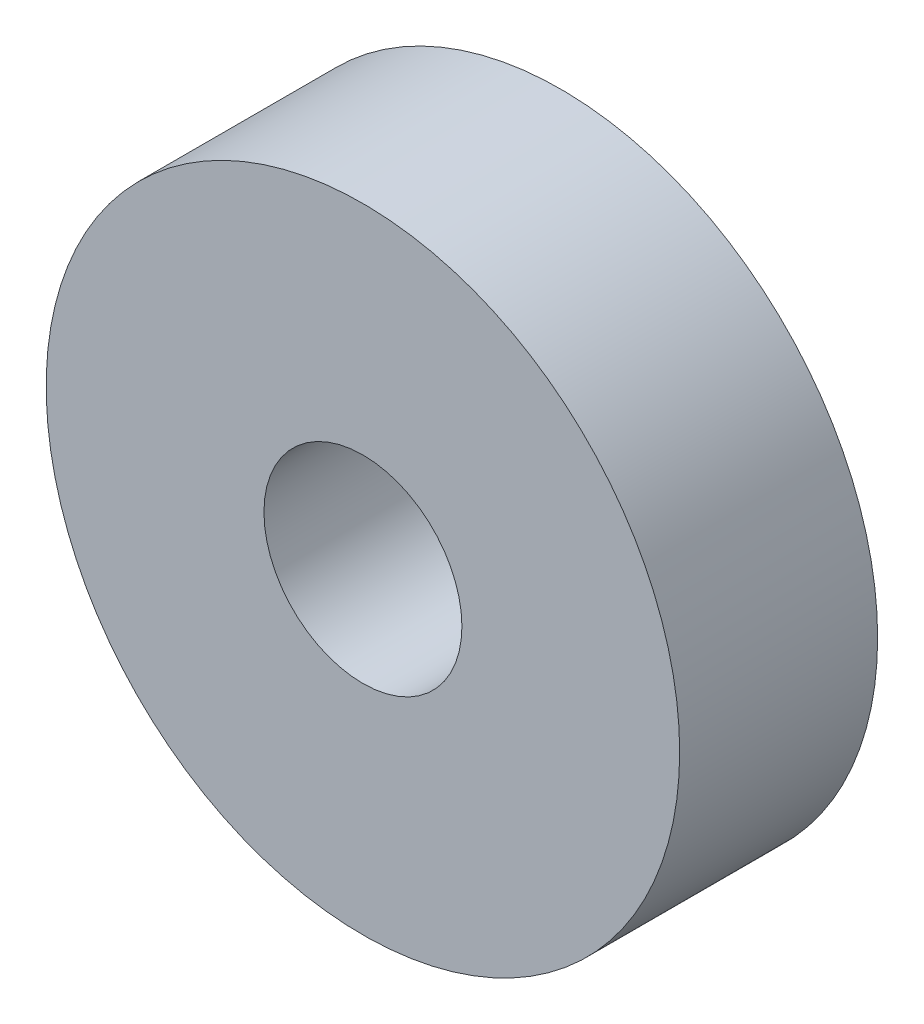
SolidWorks part; units mm, degrees
ref_plane "Front Plane" through (0, 0, 0) normal (0, 0, 1) x (1, 0, 0)
ref_plane "Top Plane" through (0, 0, 0) normal (0, 1, 0) x (1, 0, 0)
ref_plane "Right Plane" through (0, 0, 0) normal (1, 0, 0) x (0, 0, -1)
sketch "Sketch1" plane through (0, 0, 0) normal (0, 0, 1) x (1, 0, 0)
  circle A0 centre (0, 0) radius 2.5
  circle A1 centre (0, 0) radius 8
  dimension "D1" = 5
  dimension "D2" = 16
extrude "Boss-Extrude1" add sketch "Sketch1" along normal blind 5
